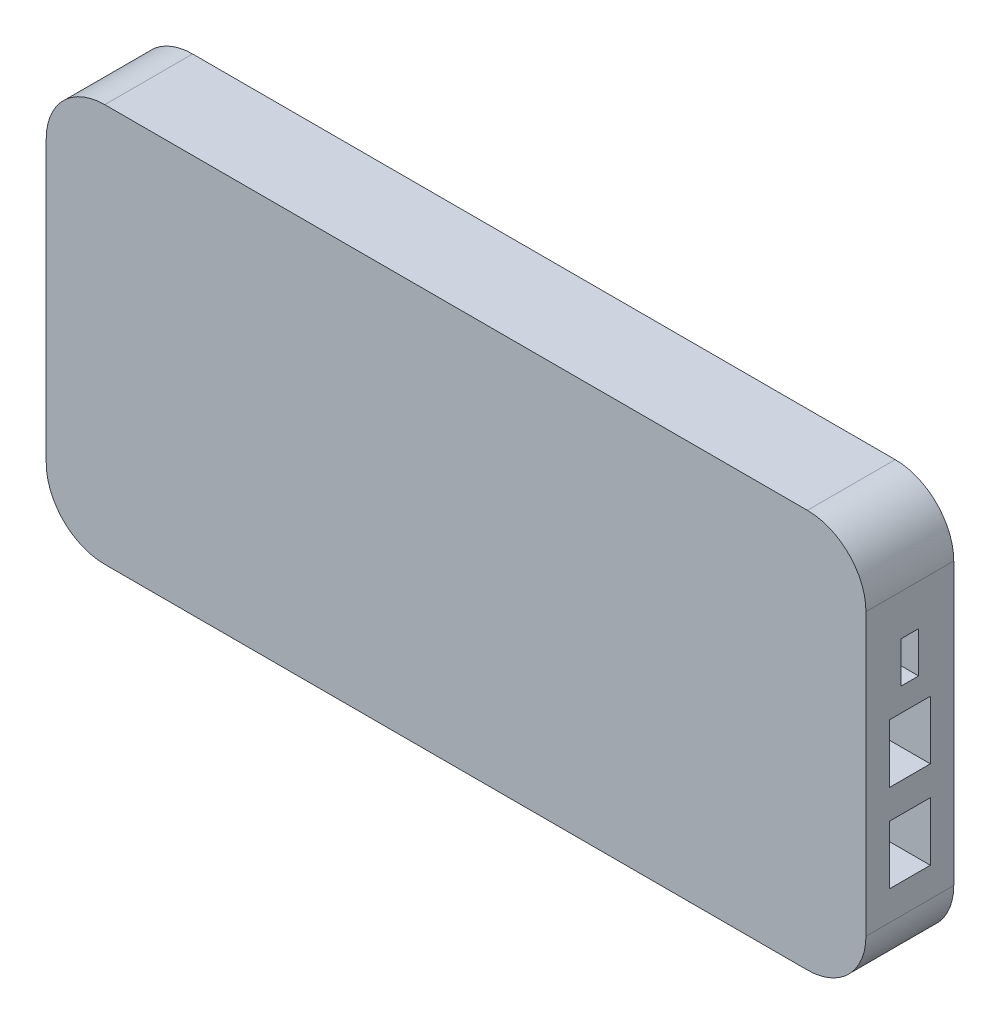
SolidWorks part; units mm, degrees
material "PA Tip 6"
ref_plane "Ön Düzlem" through (0, 0, 0) normal (0, 0, 1) x (1, 0, 0)
ref_plane "Üst Düzlem" through (0, 0, 0) normal (0, 1, 0) x (1, 0, 0)
ref_plane "Sağ Düzlem" through (0, 0, 0) normal (1, 0, 0) x (0, 0, -1)
sketch "Çizim1" plane through (0, 0, 0) normal (0, 0, 1) x (1, 0, 0)
  line L1 (10, 0) -> (130, 0)
  line L2 (0, 10) -> (0, 58)
  line L3 (10, 68) -> (130, 68)
  line L4 (140, 10) -> (140, 58)
  arc A0 (130, 0) -> (140, 10) centre (130, 10) ccw
  arc A1 (10, 0) -> (0, 10) centre (10, 10) cw
  arc A2 (130, 68) -> (140, 58) centre (130, 58) cw
  arc A3 (10, 68) -> (0, 58) centre (10, 58) ccw
  point P7 (140, 0)
  point P10 (0, 0)
  point P13 (140, 68)
  point P16 (0, 68)
  dimension "D3" = 10
  dimension "D1" = 140
  dimension "D2" = 68
extrude "Yükseklik-Ekstrüzyon1" add sketch "Çizim1" along normal blind 15
sketch "Çizim2" plane through (140, 0, 0) normal (1, 0, 0) x (0, 0, -1)
  line L1 (-11, 25) -> (-4, 25)
  line L2 (-11, 25) -> (-11, 15)
  line L3 (-11, 15) -> (-4, 15)
  line L4 (-4, 25) -> (-4, 15)
  line L5 (-15, 10) -> (-15, 58) construction
  line L6 (-15, 10) -> (0, 10) construction
  line L7 (-11, 40) -> (-4, 40)
  line L8 (-11, 40) -> (-11, 30)
  line L9 (-11, 30) -> (-4, 30)
  line L10 (-4, 40) -> (-4, 30)
  line L12 (-9, 51) -> (-6, 51)
  line L13 (-9, 51) -> (-9, 44)
  line L14 (-9, 44) -> (-6, 44)
  line L15 (-6, 51) -> (-6, 44)
  dimension "D1" = 10
  dimension "D2" = 7
  dimension "D3" = 4
  dimension "D4" = 7
  dimension "D5" = 10
  dimension "D6" = 4
  dimension "D7" = 5
  dimension "D8" = 5
  dimension "D9" = 7
  dimension "D10" = 3
  dimension "D11" = 4
  dimension "D12" = 6
extrude "Kes-Ekstrüzyon1" cut sketch "Çizim2" against normal blind 10
